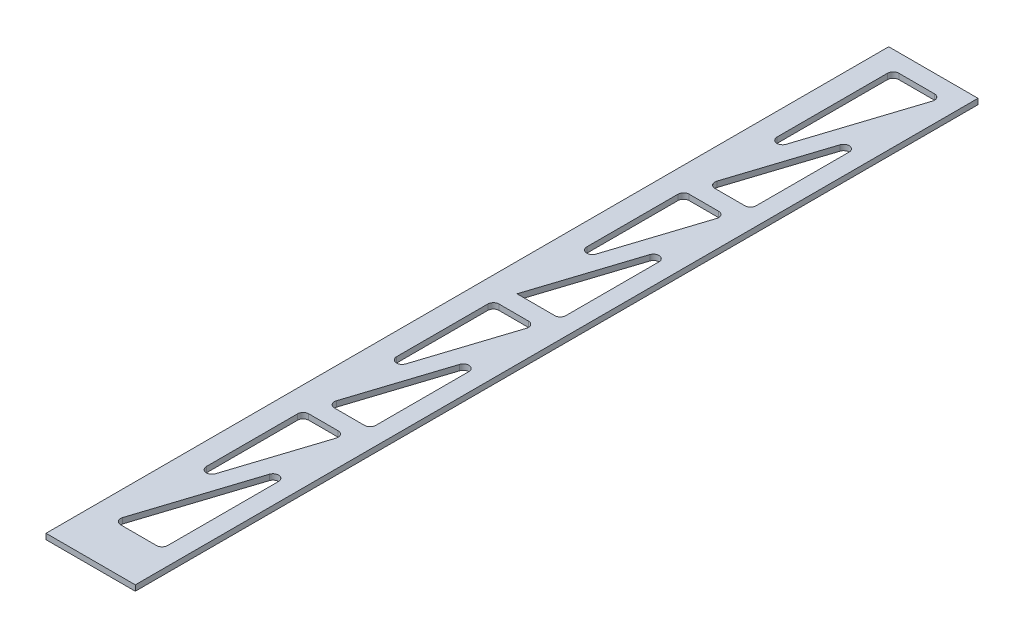
SolidWorks part; units mm, degrees
ref_plane "Front Plane" through (0, 0, 0) normal (0, 0, 1) x (1, 0, 0)
ref_plane "Top Plane" through (0, 0, 0) normal (0, 1, 0) x (1, 0, 0)
ref_plane "Right Plane" through (0, 0, 0) normal (1, 0, 0) x (0, 0, -1)
sketch "Sketch1" plane through (0, 0, 0) normal (0, 1, 0) x (1, 0, 0)
  line L1 (-12.7, -119.8562) -> (12.7, -119.8562)
  line L2 (-12.7, -119.8562) -> (-12.7, 119.8563)
  line L3 (-12.7, 119.8563) -> (12.7, 119.8563)
  line L4 (12.7, -119.8562) -> (12.7, 119.8563)
  line L5 (-12.7, -119.8562) -> (12.7, 119.8563) construction
  line L6 (-12.7, 119.8563) -> (12.7, -119.8562) construction
  point P0 (0, 0)
extrude "Boss-Extrude1" add sketch "Sketch1" along normal blind 1.5875
sketch "Sketch2" plane through (0, 1.5875, 0) normal (0, 1, 0) x (1, 0, 0)
  line L0 (-6.35, -114.7585) -> (-6.35, -107.1562) construction
  line L1 (7.62, -114.7585) -> (7.62, -63.9486) construction
  line L2 (-12.7, 119.8563) -> (-12.7, -119.8562) construction
  line L3 (12.7, -119.8562) -> (12.7, 119.8563) construction
  line L4 (-4.1683, -107.1562) -> (6.0325, -107.1562)
  line L5 (-12.7, -119.8562) -> (12.7, -119.8562) construction
  line L6 (-4.7625, 114.7763) -> (5.408, 114.7763)
  line L7 (12.7, 119.8563) -> (-12.7, 119.8563) construction
  line L8 (-6.35, 113.1888) -> (-6.35, 81.7326)
  line L9 (7.62, 88.2872) -> (7.62, 61.8172)
  line L10 (-5.6788, -105.0804) -> (4.522, -73.5304)
  line L11 (-3.252, -81.0617) -> (5.1323, -55.1301)
  line L12 (-3.252, -26.9597) -> (5.1323, -1.0281)
  line L13 (-4.0363, -45.8984) -> (4.522, -19.4284)
  line L14 (-3.252, 27.1423) -> (5.1323, 53.0739)
  line L15 (-4.7075, 6.1277) -> (4.522, 34.6736)
  line L16 (-3.252, 81.2443) -> (6.9185, 112.7004)
  line L17 (-4.0363, 62.3056) -> (4.522, 88.7756)
  line L18 (-4.7625, -53.0542) -> (3.6218, -53.0542)
  line L19 (-2.5258, -47.9742) -> (6.0325, -47.9742)
  line L20 (-4.7075, 6.1277) -> (6.0325, 6.1278)
  line L21 (-4.7625, 1.0478) -> (3.6218, 1.0478)
  line L22 (-2.5258, 60.2297) -> (6.0325, 60.2297)
  line L23 (-4.7625, 55.1498) -> (3.6218, 55.1498)
  line L24 (-6.35, 71.6625) -> (-6.35, 142.4598) construction
  line L25 (-6.35, 53.5623) -> (-6.35, 27.6306)
  line L26 (7.62, 60.2298) -> (7.62, 98.3574) construction
  line L27 (7.62, 34.1852) -> (7.62, 7.7153)
  line L28 (-6.35, -36.5415) -> (-6.35, 1.0478) construction
  line L29 (-6.35, -54.6417) -> (-6.35, -80.5734)
  line L30 (7.62, -47.9742) -> (7.62, -9.8466) construction
  line L31 (7.62, -74.0188) -> (7.62, -105.5687)
  line L32 (-6.35, -90.6435) -> (-6.35, -53.0542) construction
  line L33 (7.62, 114.7763) -> (7.62, 139.5943) construction
  line L34 (-6.35, -0.5397) -> (-6.35, -26.4714)
  line L35 (-6.35, 17.5605) -> (-6.35, 55.1498) construction
  line L36 (7.62, -19.9168) -> (7.62, -46.3867)
  line L37 (7.62, 6.1278) -> (7.62, 44.2554) construction
  arc A0 (-4.1683, -107.1562) -> (-5.6788, -105.0804) centre (-4.1683, -105.5687) cw
  arc A1 (7.62, -105.5687) -> (6.0325, -107.1562) centre (6.0325, -105.5687) cw
  arc A2 (-6.35, -80.5734) -> (-3.252, -81.0617) centre (-4.7625, -80.5734) ccw
  arc A3 (7.62, -74.0188) -> (4.522, -73.5304) centre (6.0325, -74.0188) ccw
  arc A4 (3.6218, -53.0542) -> (5.1323, -55.1301) centre (3.6218, -54.6417) cw
  arc A5 (-6.35, -54.6417) -> (-4.7625, -53.0542) centre (-4.7625, -54.6417) cw
  arc A6 (-2.5258, -47.9742) -> (-4.0363, -45.8984) centre (-2.5258, -46.3867) cw
  arc A7 (6.0325, -47.9742) -> (7.62, -46.3867) centre (6.0325, -46.3867) ccw
  arc A8 (7.62, -19.9168) -> (4.522, -19.4284) centre (6.0325, -19.9168) ccw
  arc A9 (-6.35, -26.4714) -> (-3.252, -26.9597) centre (-4.7625, -26.4714) ccw
  arc A10 (-4.7625, 1.0478) -> (-6.35, -0.5397) centre (-4.7625, -0.5397) ccw
  arc A11 (5.1323, -1.0281) -> (3.6218, 1.0478) centre (3.6218, -0.5397) ccw
  arc A12 (7.62, 7.7153) -> (6.0325, 6.1278) centre (6.0325, 7.7153) cw
  arc A13 (-6.35, 27.6306) -> (-3.252, 27.1423) centre (-4.7625, 27.6306) ccw
  arc A14 (7.62, 34.1852) -> (4.522, 34.6736) centre (6.0325, 34.1852) ccw
  arc A15 (3.6218, 55.1498) -> (5.1323, 53.0739) centre (3.6218, 53.5623) cw
  arc A16 (-4.7625, 55.1498) -> (-6.35, 53.5623) centre (-4.7625, 53.5623) ccw
  arc A17 (-2.5258, 60.2297) -> (-4.0363, 62.3056) centre (-2.5258, 61.8173) cw
  arc A18 (6.0325, 60.2297) -> (7.62, 61.8172) centre (6.0325, 61.8172) ccw
  arc A19 (4.522, 88.7756) -> (7.62, 88.2872) centre (6.0325, 88.2872) cw
  arc A20 (-6.35, 81.7326) -> (-3.252, 81.2443) centre (-4.7625, 81.7326) ccw
  arc A21 (-4.7625, 114.7763) -> (-6.35, 113.1888) centre (-4.7625, 113.1887) ccw
  arc A22 (6.9185, 112.7004) -> (5.408, 114.7763) centre (5.408, 113.1888) ccw
  point P42 (7.62, -107.1562)
  point P97 (-6.35, 114.7763)
extrude "Cut-Extrude1" cut sketch "Sketch2" against normal blind 1.5875
